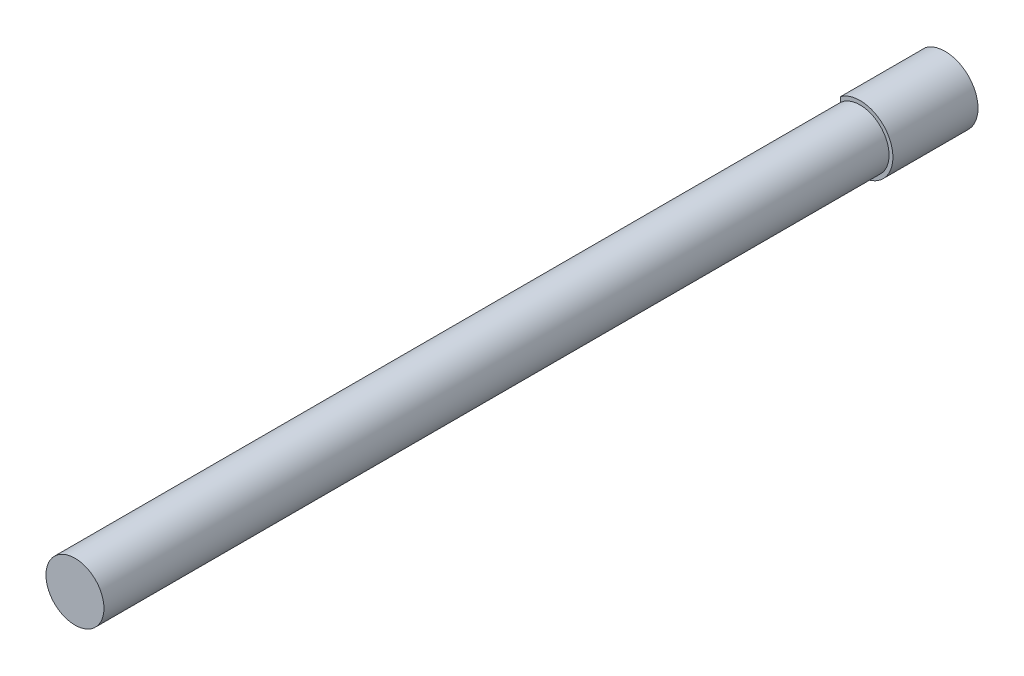
SolidWorks part; units mm, degrees
ref_plane "Front Plane" through (0, 0, 0) normal (0, 0, 1) x (1, 0, 0)
ref_plane "Top Plane" through (0, 0, 0) normal (0, 1, 0) x (1, 0, 0)
ref_plane "Right Plane" through (0, 0, 0) normal (1, 0, 0) x (0, 0, -1)
sketch "Sketch1" plane through (0, 0, 0) normal (0, 0, 1) x (1, 0, 0)
  line L0 (-2.5, 3.4369) -> (-2.5, -3.4369)
  arc A0 (-2.5, -3.4369) -> (-2.5, 3.4369) centre (0, 0) ccw
  dimension "D1" = 2.5
  dimension "D2" = 8.5
extrude "Boss-Extrude1" add sketch "Sketch1" along normal blind 10
sketch "Sketch2" plane through (0, 0, 10) normal (0, 0, 1) x (1, 0, 0)
  circle A0 centre (0, 0) radius 4.25
extrude "Boss-Extrude2" add sketch "Sketch2" along normal blind 20
sketch "Sketch3" plane through (0, 0, 0) normal (0, 0, -1) x (-1, 0, 0)
  line L1 (2.5, -3.4369) -> (2.5, 3.4369)
  line L2 (2.5, -3.4369) -> (2.5, 3.4369)
  arc A1 (2.5, 3.4369) -> (2.5, -3.4369) centre (0, 0) ccw
  arc A2 (2.5, 3.4369) -> (2.5, -3.4369) centre (0, 0) ccw
  dimension "D1" = 0
extrude "Boss-Extrude3" add sketch "Sketch3" along normal blind 1
sketch "Sketch5" plane through (0, 0, 30) normal (0, 0, 1) x (1, 0, 0)
  circle A0 centre (0, 0) radius 3.75
  circle A1 centre (0, 0) radius 4.25
  circle A2 centre (0, 0) radius 4.25
  dimension "D1" = 0
  dimension "D2" = 0.5
extrude "Cut-Extrude1" cut sketch "Sketch5" against normal up to surface (20 mm away) up to face at (-2.5, 3.4369, 10)
sketch "Sketch6" plane through (0, 0, 30) normal (0, 0, 1) x (1, 0, 0)
  circle A1 centre (0, 0) radius 3.75
  circle A2 centre (0, 0) radius 3.75
  dimension "D1" = 0
extrude "Boss-Extrude4" add sketch "Sketch6" along normal blind 81.5
